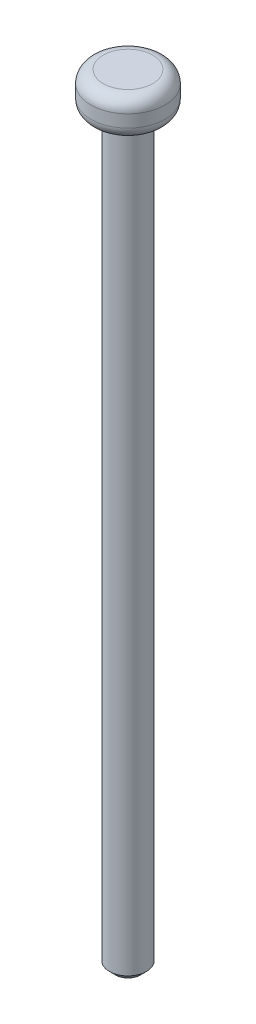
SolidWorks part; units mm, degrees
ref_plane "Front Plane" through (0, 0, 0) normal (0, 0, 1) x (1, 0, 0)
ref_plane "Top Plane" through (0, 0, 0) normal (0, 1, 0) x (1, 0, 0)
ref_plane "Right Plane" through (0, 0, 0) normal (1, 0, 0) x (0, 0, -1)
sketch "Sketch2" plane through (0, 0, 0) normal (0, 0, 1) x (1, 0, 0)
  line L0 (0, 0) -> (0.15, 0)
  line L1 (0.15, 0) -> (0.15, 6)
  line L2 (0.15, 6) -> (0.3, 6)
  line L3 (0.3, 6) -> (0.3, 6.3)
  line L4 (0.3, 6.3) -> (0, 6.3)
  line L5 (0, 6.3) -> (0, 0)
  dimension "D1" = 0.15
  dimension "D2" = 0.3
  dimension "D3" = 0.3
  dimension "D4" = 6
revolve "Revolve1" add sketch "Sketch2" angle 360 about L5
fillet "Fillet1" radius 0.1 2 edges at (-0.3, 6, 0) (-0.3, 6.3, 0)
chamfer "Chamfer1" distance 0.05 angle 45 1 edges at (-0.15, 0, 0)
